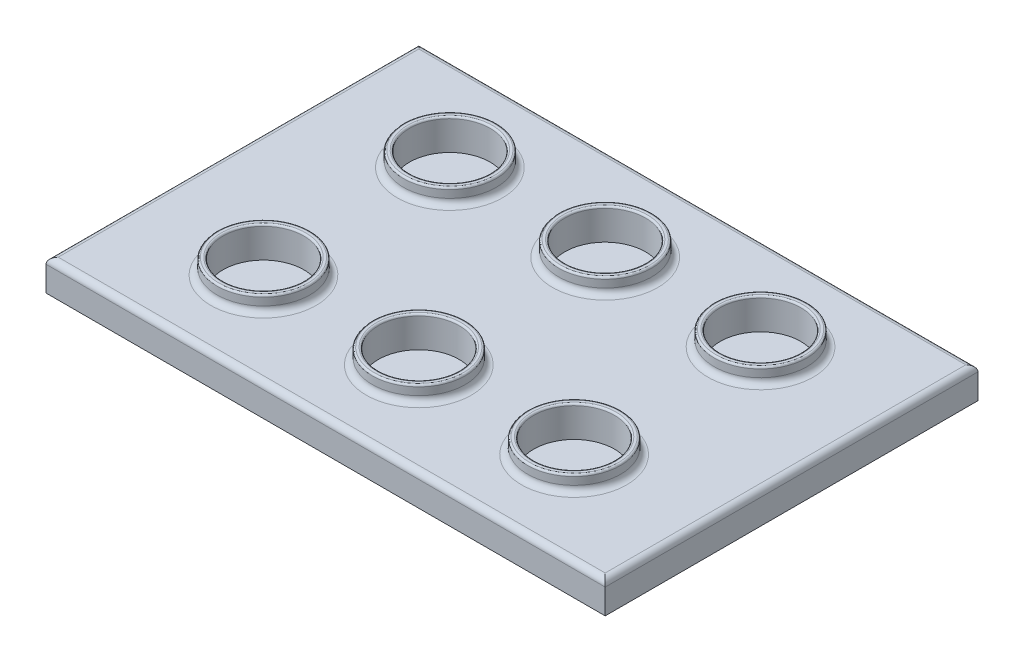
SolidWorks part; units mm, degrees
material "ABS"
ref_plane "Front Plane" through (0, 0, 0) normal (0, 0, 1) x (1, 0, 0)
ref_plane "Top Plane" through (0, 0, 0) normal (0, 1, 0) x (1, 0, 0)
ref_plane "Right Plane" through (0, 0, 0) normal (1, 0, 0) x (0, 0, -1)
sketch "Sketch1" plane through (0, 0, 0) normal (0, 1, 0) x (1, 0, 0)
  line L1 (-114.3, -76.2) -> (114.3, -76.2)
  line L2 (-114.3, -76.2) -> (-114.3, 76.2)
  line L3 (-114.3, 76.2) -> (114.3, 76.2)
  line L4 (114.3, -76.2) -> (114.3, 76.2)
  line L5 (-114.3, -76.2) -> (114.3, 76.2) construction
  line L6 (-114.3, 76.2) -> (114.3, -76.2) construction
  point P0 (0, 0)
  dimension "D1" = 152.4
  dimension "D2" = 228.6
extrude "Boss-Extrude1" add sketch "Sketch1" along normal blind 12.7
sketch "Sketch2" plane through (0, 12.7, 0) normal (0, 1, 0) x (1, 0, 0)
  line L0 (-114.3, 76.2) -> (-114.3, -76.2) construction
  line L1 (-114.3, -76.2) -> (114.3, -76.2) construction
  line L2 (-63.5, -38.1) -> (0, -38.1) construction
  line L3 (-63.5, -38.1) -> (-63.5, 38.1) construction
  circle A0 centre (-63.5, -38.1) radius 16.51
  circle A1 centre (0, -38.1) radius 16.51
  circle A2 centre (63.5, -38.1) radius 16.51
  circle A3 centre (0, 38.1) radius 16.51
  circle A4 centre (63.5, 38.1) radius 16.51
  circle A5 centre (-63.5, 38.1) radius 16.51
  point P2 (-39.4271, 46.8975)
  dimension "D1" = 33.02
  dimension "D2" = 50.8
  dimension "D3" = 38.1
  dimension "D6" = 63.5
  dimension "D7" = 76.2
  dimension "D4" = 3
  dimension "D5" = 2
extrude "Cut-Extrude1" cut sketch "Sketch2" against normal blind 6.35
sketch "Sketch3" plane through (0, 12.7, 0) normal (0, 1, 0) x (1, 0, 0)
  circle A0 centre (63.5, 38.1) radius 16.51 construction
  circle A1 centre (63.5, -38.1) radius 16.51 construction
  circle A2 centre (0, -38.1) radius 16.51 construction
  circle A3 centre (0, 38.1) radius 16.51 construction
  circle A4 centre (-63.5, 38.1) radius 16.51 construction
  circle A5 centre (-63.5, -38.1) radius 16.51 construction
  circle A6 centre (63.5, 38.1) radius 16.51
  circle A7 centre (63.5, -38.1) radius 16.51
  circle A8 centre (0, -38.1) radius 16.51
  circle A9 centre (0, 38.1) radius 16.51
  circle A10 centre (-63.5, 38.1) radius 16.51
  circle A11 centre (-63.5, -38.1) radius 16.51
  circle A12 centre (-63.5, 38.1) radius 19.01
  circle A14 centre (0, 38.1) radius 19.01
  circle A15 centre (63.5, 38.1) radius 19.01
  circle A16 centre (63.5, -38.1) radius 19.01
  circle A17 centre (0, -38.1) radius 19.01
  circle A18 centre (-63.5, -38.1) radius 19.01
  dimension "D1" = 2.5
extrude "Boss-Extrude2" add sketch "Sketch3" along normal blind 6.35
fillet "Fillet1" radius 0.75 12 edges at (-63.5, 19.05, -21.59) (-63.5, 19.05, -19.09) (0, 19.05, -21.59) (0, 19.05, -19.09) (63.5, 19.05, -21.59) (63.5, 19.05, -19.09) (63.5, 19.05, 54.61) (63.5, 19.05, 57.11) (0, 19.05, 54.61) (0, 19.05, 57.11) (-63.5, 19.05, 54.61) (-63.5, 19.05, 57.11)
fillet "Fillet2" radius 2.5 10 edges at (-63.5, 12.7, 19.09) (63.5, 12.7, 19.09) (0, 12.7, -57.11) (0, 12.7, 76.2) (-114.3, 12.7, 0) (0, 12.7, -76.2) (114.3, 12.7, 0) (-63.5, 12.7, -57.11) (63.5, 12.7, -57.11) (0, 12.7, 19.09)
